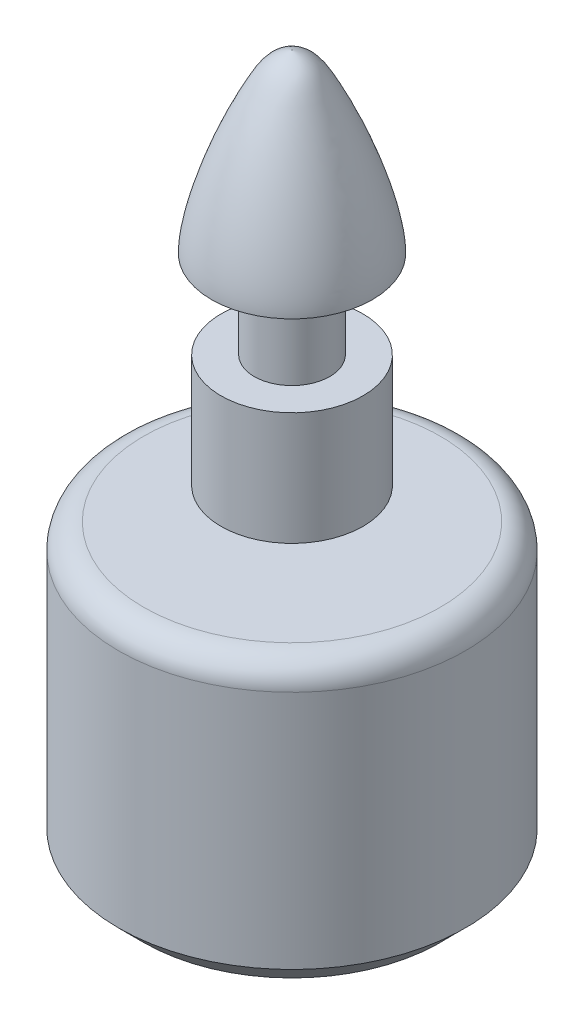
SolidWorks part; units mm, degrees
material "6061 合金"
ref_plane "前基準面" through (0, 0, 0) normal (0, 0, 1) x (1, 0, 0)
ref_plane "上基準面" through (0, 0, 0) normal (0, 1, 0) x (1, 0, 0)
ref_plane "右基準面" through (0, 0, 0) normal (1, 0, 0) x (0, 0, -1)
sketch "草圖1" plane through (0, 0, 0) normal (0, 1, 0) x (1, 0, 0)
  line L0 (0, 13.8) -> (0, -13.8) construction
  line L1 (-13.8, 0) -> (13.8, 0) construction
  circle A0 centre (0, 0) radius 13.8
  circle A1 centre (0, 9.5) radius 1.25
  circle A2 centre (0, -9.5) radius 1.25
  circle A3 centre (8, 0) radius 1.25
  circle A4 centre (-8, 0) radius 1.25
  dimension "D1" = 27.6
  dimension "D2" = 2.5
  dimension "D3" = 8
  dimension "D4" = 8
  dimension "D5" = 9.5
  dimension "D6" = 9.5
extrude "填料-伸長1" add sketch "草圖1" along normal blind 4.6
sketch "草圖2" plane through (0, 4.6, 0) normal (0, 1, 0) x (1, 0, 0)
  circle A0 centre (0, 0) radius 13.8
extrude "填料-伸長2" add sketch "草圖2" along normal blind 18.5
fillet "圓角1" radius 2 1 edges at (0, 23.1, 13.8)
sketch "草圖4" plane through (0, 23.1, 0) normal (0, 1, 0) x (1, 0, 0)
  circle A0 centre (0, 0) radius 3
  dimension "D1" = 6
sketch "草圖5" plane through (0, 0, 0) normal (0, 0, 1) x (1, 0, 0)
  line L0 (0, 23.1) -> (0, 55.6)
  line L1 (3, 23.1) -> (-3, 23.1) construction
  line L3 (-5.65, 25.6) -> (-5.65, 34.6)
  line L4 (-5.65, 34.6) -> (-3, 34.6)
  line L5 (-3, 34.6) -> (-3, 41.6)
  line L6 (-3, 41.6) -> (-6.4, 41.6)
  line L7 (-5.65, 25.6) -> (-1.5, 25.6)
  line L8 (-1.5, 25.6) -> (-1.5, 23.1)
  line L9 (-1.5, 23.1) -> (0, 23.1)
  spline S0 degree 3 poles (0, 55.6) (-0.4481, 55.4841) (-1.5233, 55.0799) (-4.6523, 49.5713) (-6.4, 43.7972) (-6.4, 41.6) knots 0 0 0 0 0.157071 0.257071 1 1 1 1
  dimension "D1" = 9
  dimension "D2" = 7
  dimension "D3" = 14
  dimension "D4" = 6.4
  dimension "D5" = 3
  dimension "D6" = 5.65
  dimension "D7" = 2.5
  dimension "D8" = 1.5
revolve "旋轉1" add sketch "草圖5" angle 360 about L0
chamfer "導角1" distance 2 angle 45 1 edges at (0, 0, 13.8)
